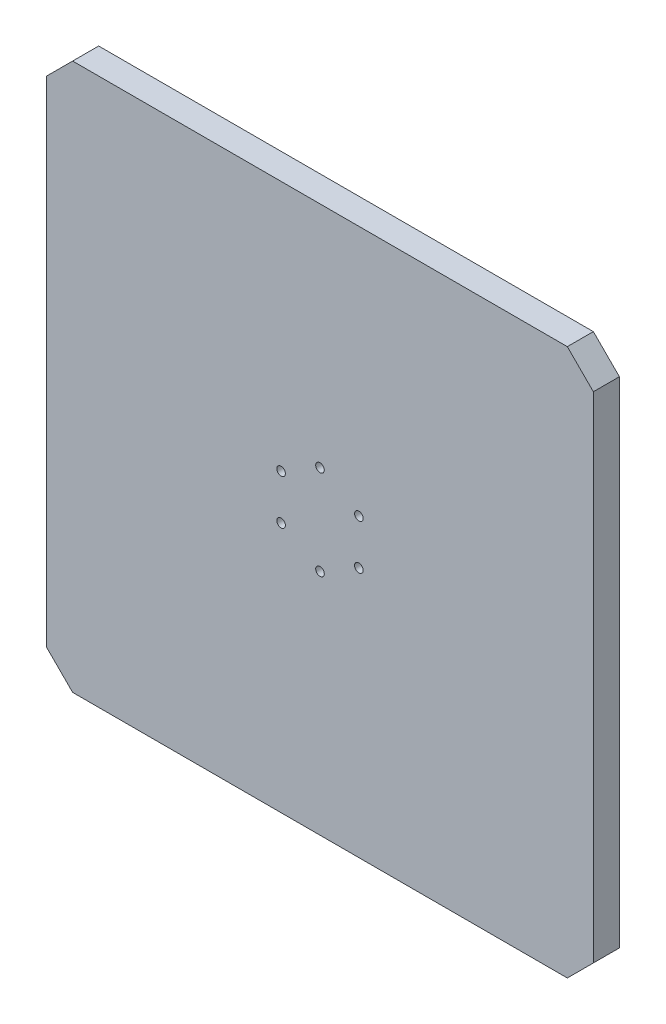
SolidWorks part; units mm, degrees
ref_plane "前视基准面" through (0, 0, 0) normal (0, 0, 1) x (1, 0, 0)
ref_plane "上视基准面" through (0, 0, 0) normal (0, 1, 0) x (1, 0, 0)
ref_plane "右视基准面" through (0, 0, 0) normal (1, 0, 0) x (0, 0, -1)
sketch "草图1" plane through (0, 0, 0) normal (0, 0, 1) x (1, 0, 0)
  line L1 (-75, -75) -> (75, -75)
  line L2 (-75, -75) -> (-75, 75)
  line L3 (-75, 75) -> (75, 75)
  line L4 (75, -75) -> (75, 75)
  line L5 (-75, -75) -> (75, 75) construction
  line L6 (-75, 75) -> (75, -75) construction
  point P0 (0, 0)
  dimension "D1" = 150
  dimension "D2" = 150
extrude "凸台-拉伸1" add sketch "草图1" along normal blind 30
sketch "草图2" plane through (0, 0, 0) normal (0, 0, -1) x (-1, 0, 0)
  circle A0 centre (0, 0) radius 48.25
  dimension "D1" = 96.5
extrude "凸台-拉伸2" add sketch "草图2" along normal blind 10
sketch "草图3" plane through (0, 0, -10) normal (0, 0, -1) x (-1, 0, 0)
  circle A1 centre (0, 17.25) radius 1.65
  circle A2 centre (14.9389, 8.625) radius 1.65
  circle A3 centre (14.9389, -8.625) radius 1.65
  circle A4 centre (0, -17.25) radius 1.65
  circle A5 centre (-14.9389, -8.625) radius 1.65
  circle A6 centre (-14.9389, 8.625) radius 1.65
  point P18 (0, 0)
  dimension "D2" = 3.3
  dimension "D3" = 6
extrude "凸台-拉伸3" add sketch "草图3" along normal blind 8.3
sketch "草图4" plane through (0, 75, 0) normal (0, 1, 0) x (1, 0, 0)
  line L4 (75, 0) -> (-75, 0)
  line L5 (-75, 0) -> (-75, -30)
  line L6 (-75, -30) -> (75, -30)
  line L7 (75, -30) -> (75, 0)
  line L8 (75, 0) -> (-75, 0)
  line L9 (-75, 0) -> (-75, -30)
  line L10 (-75, -30) -> (75, -30)
  line L11 (75, -30) -> (75, 0)
  dimension "D1" = 0
extrude "凸台-拉伸4" add sketch "草图4" along normal blind 30
sketch "草图5" plane through (-75, 0, 0) normal (-1, 0, 0) x (0, 0, 1)
  line L4 (0, 105) -> (0, -75)
  line L5 (0, -75) -> (30, -75)
  line L6 (30, -75) -> (30, 105)
  line L7 (30, 105) -> (0, 105)
  line L8 (0, 105) -> (0, -75)
  line L9 (0, -75) -> (30, -75)
  line L10 (30, -75) -> (30, 105)
  line L11 (30, 105) -> (0, 105)
  dimension "D1" = 0
extrude "凸台-拉伸5" add sketch "草图5" along normal blind 30
sketch "草图6" plane through (0, -75, 0) normal (0, -1, 0) x (1, 0, 0)
  line L4 (-105, 0) -> (75, 0)
  line L5 (75, 0) -> (75, 30)
  line L6 (75, 30) -> (-105, 30)
  line L7 (-105, 30) -> (-105, 0)
  line L8 (-105, 0) -> (75, 0)
  line L9 (75, 0) -> (75, 30)
  line L10 (75, 30) -> (-105, 30)
  line L11 (-105, 30) -> (-105, 0)
  dimension "D1" = 0
extrude "凸台-拉伸6" add sketch "草图6" along normal blind 30
sketch "草图7" plane through (75, 0, 0) normal (1, 0, 0) x (0, 0, -1)
  line L4 (0, -105) -> (0, 105)
  line L5 (0, 105) -> (-30, 105)
  line L6 (-30, 105) -> (-30, -105)
  line L7 (-30, -105) -> (0, -105)
  line L8 (0, -105) -> (0, 105)
  line L9 (0, 105) -> (-30, 105)
  line L10 (-30, 105) -> (-30, -105)
  line L11 (-30, -105) -> (0, -105)
  dimension "D1" = 0
extrude "凸台-拉伸7" add sketch "草图7" along normal blind 30
chamfer "倒角1" distance 10 angle 45 4 edges at (-105, 105, 15) (-105, -105, 15) (105, -105, 15) (105, 105, 15)
sketch "草图8" plane through (0, 0, -10) normal (0, 0, -1) x (-1, 0, 0)
  circle A0 centre (-14.9389, -8.625) radius 1.65 construction
  circle A1 centre (0, -17.25) radius 1.65 construction
  circle A2 centre (14.9389, -8.625) radius 1.65 construction
  circle A3 centre (14.9389, 8.625) radius 1.65 construction
  circle A4 centre (0, 17.25) radius 1.65 construction
  circle A5 centre (-14.9389, 8.625) radius 1.65 construction
  circle A6 centre (-14.9389, -8.625) radius 1.65
  circle A7 centre (0, -17.25) radius 1.65
  circle A8 centre (14.9389, -8.625) radius 1.65
  circle A9 centre (14.9389, 8.625) radius 1.65
  circle A10 centre (0, 17.25) radius 1.65
  circle A11 centre (-14.9389, 8.625) radius 1.65
extrude "切除-拉伸1" cut sketch "草图8" against normal through all and the other way through all
sketch "草图9" plane through (0, 0, 0) normal (0, 0, -1) x (-1, 0, 0)
  line L8 (-95, -105) -> (95, -105)
  line L9 (95, -105) -> (105, -95)
  line L10 (105, -95) -> (105, 95)
  line L11 (105, 95) -> (95, 105)
  line L12 (95, 105) -> (-95, 105)
  line L13 (-95, 105) -> (-105, 95)
  line L14 (-105, 95) -> (-105, -95)
  line L15 (-105, -95) -> (-95, -105)
  line L16 (-95, -105) -> (95, -105)
  line L17 (95, -105) -> (105, -95)
  line L18 (105, -95) -> (105, 95)
  line L19 (105, 95) -> (95, 105)
  line L20 (95, 105) -> (-95, 105)
  line L21 (-95, 105) -> (-105, 95)
  line L22 (-105, 95) -> (-105, -95)
  line L23 (-105, -95) -> (-95, -105)
  circle A0 centre (0, 0) radius 48.25 construction
  circle A1 centre (0, 0) radius 48.25
  dimension "D1" = 0
extrude "切除-拉伸2" cut sketch "草图9" against normal blind 15
sketch "草图10" plane through (0, 0, -10) normal (0, 0, -1) x (-1, 0, 0)
  circle A1 centre (0, 0) radius 48.25
  circle A2 centre (0, 0) radius 48.25
  dimension "D1" = 0
extrude "切除-拉伸3" cut sketch "草图10" against normal blind 15
sketch "草图11" plane through (0, 0, 5) normal (0, 0, -1) x (-1, 0, 0)
  circle A1 centre (0, 0) radius 48.25
  circle A2 centre (0, 0) radius 48.25
  dimension "D1" = 0
extrude "切除-拉伸4" cut sketch "草图11" against normal blind 5
sketch "草图12" plane through (0, 0, 15) normal (0, 0, -1) x (-1, 0, 0)
  line L8 (-105, -95) -> (-95, -105)
  line L9 (-95, -105) -> (95, -105)
  line L10 (95, -105) -> (105, -95)
  line L11 (105, -95) -> (105, 95)
  line L12 (105, 95) -> (95, 105)
  line L13 (95, 105) -> (-95, 105)
  line L14 (-95, 105) -> (-105, 95)
  line L15 (-105, 95) -> (-105, -95)
  line L16 (-105, -95) -> (-95, -105)
  line L17 (-95, -105) -> (95, -105)
  line L18 (95, -105) -> (105, -95)
  line L19 (105, -95) -> (105, 95)
  line L20 (105, 95) -> (95, 105)
  line L21 (95, 105) -> (-95, 105)
  line L22 (-95, 105) -> (-105, 95)
  line L23 (-105, 95) -> (-105, -95)
  circle A1 centre (0, 0) radius 48.25
  circle A2 centre (0, 0) radius 48.25
  dimension "D1" = 0
  dimension "D2" = 0
extrude "切除-拉伸5" cut sketch "草图12" against normal blind 5
